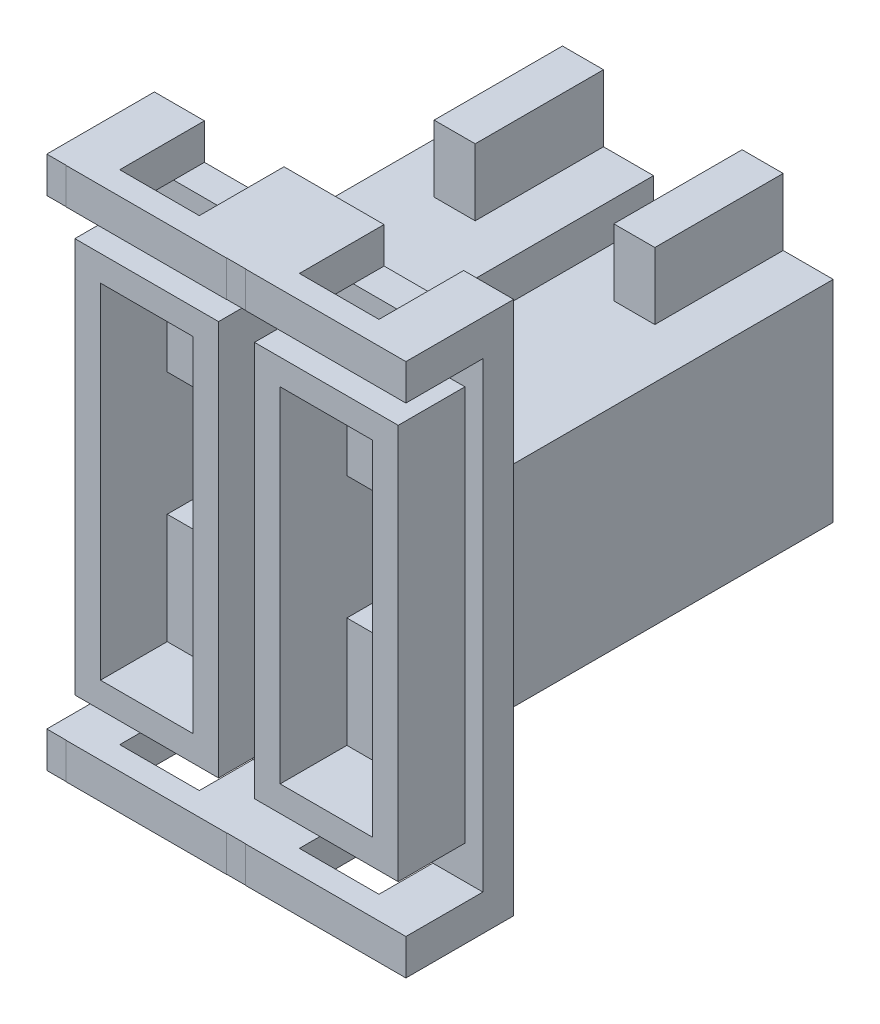
SolidWorks part; units mm, degrees
ref_plane "Спереди" through (0, 0, 0) normal (0, 0, 1) x (1, 0, 0)
ref_plane "Сверху" through (0, 0, 0) normal (0, 1, 0) x (1, 0, 0)
ref_plane "Справа" through (0, 0, 0) normal (1, 0, 0) x (0, 0, -1)
ref_plane "Плоскость1" through (0, 0, 1.05) normal (0, 0, 1) x (1, 0, 0)
sketch "Эскиз1" plane through (0, 0, 1.05) normal (0, 0, 1) x (1, 0, 0)
  line L0 (0, 5.2) -> (-3.125, 5.2)
  line L1 (-3.125, 5.2) -> (-3.125, -5.2)
  line L2 (-3.125, -5.2) -> (0, -5.2)
  line L3 (0, -5.2) -> (0, 5.2)
  dimension "D1" = 3.125
  dimension "D2" = 10.4
extrude "Бобышка-Вытянуть1" add sketch "Эскиз1" against normal blind 2.1
ref_plane "Плоскость2" through (0, 0, -0.45) normal (0, 0, -1) x (-1, 0, 0)
sketch "Эскиз2" plane through (0, 0, -0.45) normal (0, 0, -1) x (-1, 0, 0)
  line L0 (3.125, 4.5) -> (-3.125, 4.5)
  line L1 (-3.125, 4.5) -> (-3.125, -4.5)
  line L2 (-3.125, -4.5) -> (3.125, -4.5)
  line L3 (3.125, -4.5) -> (3.125, 4.5)
extrude "Вырез-Вытянуть1" cut sketch "Эскиз2" against normal up to next
sketch "Эскиз3" plane through (0, 0, -0.45) normal (0, 0, -1) x (-1, 0, 0)
  line L0 (0.975, 4.5) -> (2.525, 4.5)
  line L1 (2.525, 4.5) -> (2.525, 5.2)
  line L2 (2.525, 5.2) -> (0.975, 5.2)
  line L3 (0.975, 5.2) -> (0.975, 4.5)
extrude "Вырез-Вытянуть2" cut sketch "Эскиз3" against normal blind 1.05
sketch "Эскиз5" plane through (0, 0, -0.45) normal (0, 0, -1) x (-1, 0, 0)
  line L0 (0.975, -5.2) -> (2.525, -5.2)
  line L1 (2.525, -5.2) -> (2.525, -4.5)
  line L2 (2.525, -4.5) -> (0.975, -4.5)
  line L3 (0.975, -4.5) -> (0.975, -5.2)
extrude "Вырез-Вытянуть4" cut sketch "Эскиз5" against normal blind 1.05
ref_plane "Плоскость3" through (0, 0, -7.65) normal (0, 0, -1) x (-1, 0, 0)
sketch "Эскиз8" plane through (0, 0, -7.65) normal (0, 0, -1) x (-1, 0, 0)
  line L0 (3.125, 2.05) -> (0.375, 2.05)
  line L1 (0.375, 2.05) -> (0.375, -2.05)
  line L2 (3.125, -2.05) -> (3.125, 2.05)
  arc A0 (0.375, -2.05) -> (3.125, -2.05) centre (1.75, -3.5024) cw
extrude "Бобышка-Вытянуть3" add sketch "Эскиз8" against normal up to surface (6.6 mm away) up to face at (-1.5625, 0, -1.05)
ref_plane "Плоскость4" through (0, 0, 0.85) normal (0, 0, 1) x (1, 0, 0)
sketch "Эскиз9" plane through (0, 0, 0.85) normal (0, 0, 1) x (1, 0, 0)
  line L0 (-0.35, -3.85) -> (-0.35, 3.85)
  line L1 (-0.35, 3.85) -> (-3.15, 3.85)
  line L2 (-3.15, 3.85) -> (-3.15, -3.85)
  line L3 (-3.15, -3.85) -> (-0.35, -3.85)
extrude "Бобышка-Вытянуть4" add sketch "Эскиз9" against normal up to surface (1.3 mm away) up to face at (-1.6875, 0, -0.45)
sketch "Эскиз11" plane through (0, 0, -0.45) normal (0, 0, -1) x (-1, 0, 0)
  line L0 (0.85, 3.35) -> (0.85, -3.35)
  line L1 (0.85, -3.35) -> (2.65, -3.35)
  line L2 (2.65, -3.35) -> (2.65, 3.35)
  line L3 (2.65, 3.35) -> (0.85, 3.35)
extrude "Вырез-Вытянуть6" cut sketch "Эскиз11" against normal up to next
ref_plane "Плоскость5" through (0, 0, -5.65) normal (0, 0, -1) x (-1, 0, 0)
sketch "Эскиз14" plane through (0, 0, -5.65) normal (0, 0, -1) x (-1, 0, 0)
  line L0 (0.85, -1.2) -> (2.65, -1.2)
  line L1 (2.65, -1.2) -> (2.65, 1.2)
  line L2 (2.65, 1.2) -> (0.85, 1.2)
  line L3 (0.85, 1.2) -> (0.85, -1.2)
extrude "Вырез-Вытянуть9" cut sketch "Эскиз14" against normal up to next
ref_plane "Плоскость6" through (0, -4.5, 0) normal (0, 1, 0) x (1, 0, 0)
sketch "Эскиз16" plane through (0, -4.5, 0) normal (0, 1, 0) x (1, 0, 0)
  line L0 (-0.975, 1.05) -> (-2.525, 1.05)
  line L1 (-2.525, 1.05) -> (-2.525, 0.45)
  line L2 (-2.525, 0.45) -> (-0.975, 0.45)
  line L3 (-0.975, 0.45) -> (-0.975, 1.05)
extrude "Вырез-Вытянуть11" cut sketch "Эскиз16" against normal up to next
ref_plane "Плоскость7" through (0, 4.5, 0) normal (0, -1, 0) x (1, 0, 0)
sketch "Эскиз17" plane through (0, 4.5, 0) normal (0, -1, 0) x (1, 0, 0)
  line L0 (-2.525, -1.05) -> (-0.975, -1.05)
  line L1 (-0.975, -1.05) -> (-0.975, -0.45)
  line L2 (-0.975, -0.45) -> (-2.525, -0.45)
  line L3 (-2.525, -0.45) -> (-2.525, -1.05)
extrude "Вырез-Вытянуть12" cut sketch "Эскиз17" against normal up to next
ref_plane "Плоскость8" through (-3.5, 0, 0) normal (-1, 0, 0) x (0, -1, 0)
sketch "Эскиз19" plane through (-3.5, 0, 0) normal (-1, 0, 0) x (0, -1, 0)
  line L0 (-5.2, -1.05) -> (-2.05, -1.05) construction
  line L2 (1.65, -1.05) -> (5.2, -1.05)
  line L3 (5.2, -1.05) -> (5.2, 1.0464)
  line L4 (5.2, 1.0464) -> (4.5, 1.0464)
  line L5 (4.5, 1.0464) -> (4.5, -0.4536)
  line L6 (4.5, -0.4536) -> (-4.5, -0.4536)
  line L7 (-4.5, -0.4536) -> (-4.5, 1.0464)
  line L8 (-4.5, 1.0464) -> (-5.2, 1.0464)
  line L9 (-5.2, 1.0464) -> (-5.2, -1.05)
  line L10 (-5.2, -1.05) -> (1.65, -1.05)
extrude "Бобышка-Вытянуть6" add sketch "Эскиз19" against normal up to surface (0.375 mm away) up to face at (-3.125, 0.225, -0.75)
ref_plane "Плоскость9" through (3.5, 0, 0) normal (1, 0, 0) x (0, 0, -1)
ref_plane "Плоскость10" through (0, 3.35, 0) normal (0, 1, 0) x (1, 0, 0)
sketch "Эскиз21" plane through (0, 3.35, 0) normal (0, 1, 0) x (1, 0, 0)
  line L0 (-2.15, 7.65) -> (-2.15, 5.15)
  line L1 (-2.15, 5.15) -> (-1.35, 5.15)
  line L2 (-1.35, 5.15) -> (-1.35, 7.65)
  line L3 (-1.35, 7.65) -> (-2.15, 7.65)
extrude "Бобышка-Вытянуть8" add sketch "Эскиз21" against normal up to surface (1.3 mm away) up to face at (-2.0937, 2.05, -3.525)
hole_wizard "Диаметр отверстия Ø2.1 (2.1)2" positions "Эскиз26" profile "Эскиз25" hole size "Ø2.1" standard "Ansi Metric"
sketch "Эскиз26" plane through (0, 0, -7.65) normal (0, 0, -1) x (-1, 0, 0)
  point P0 (1.75, 0)
sketch "Эскиз25" plane through (-1.75, 0, -7.65) normal (1, 0, 0) x (0, 1, 0)
  line L0 (0, 0) -> (0, 1.2)
  line L1 (0, 1.2) -> (1.05, 1.2)
  line L2 (1.05, 1.2) -> (1.05, 0)
  line L5 (1.05, 0) -> (0, 0)
  line L10 (0, 1.2) -> (-1.05, 1.2) construction
  line L11 (0, -6.35) -> (0, 107.95) construction
  dimension "Диаметр отверстия" = 2.1
  dimension "Глубина отверстия" = 1.2
  dimension "Угол заточки сверла" = 180
hole_wizard "Диаметр отверстия Ø1.2 (1.2)1" positions "Эскиз28" profile "Эскиз27" hole size "Ø1.2" standard "Ansi Metric" end condition through all
sketch "Эскиз28" plane through (0, 0, -5.65) normal (0, 0, 1) x (1, 0, 0)
  point P0 (-1.75, 0)
sketch "Эскиз27" plane through (-1.75, 0, -5.65) normal (1, 0, 0) x (0, -1, 0)
  line L0 (0, 0) -> (0, 2)
  line L1 (0, 2) -> (0.6, 2)
  line L2 (0.6, 2) -> (0.6, 0)
  line L5 (0.6, 0) -> (0, 0)
  line L11 (0, -6.35) -> (0, 107.95) construction
  dimension "Диаметр сквозного отверстия" = 1.2
  dimension "Глубина сквозного отверстия" = 2
fillet "Скругление1" radius 0.4 1 edges at (-2.8, 0, -6.45)
pattern_linear "Линейный массив1" count 2 spacing 3.5 along (-1, 0, 0) of "Бобышка-Вытянуть1", "Вырез-Вытянуть1", "Вырез-Вытянуть2", "Вырез-Вытянуть4", "Бобышка-Вытянуть3", "Бобышка-Вытянуть4", "Вырез-Вытянуть6", "Вырез-Вытянуть9", "Вырез-Вытянуть11", "Вырез-Вытянуть12", "Бобышка-Вытянуть6", "Бобышка-Вытянуть8", "Диаметр отверстия Ø2.1 (2.1)2", "Диаметр отверстия Ø1.2 (1.2)1", "Скругление1"
